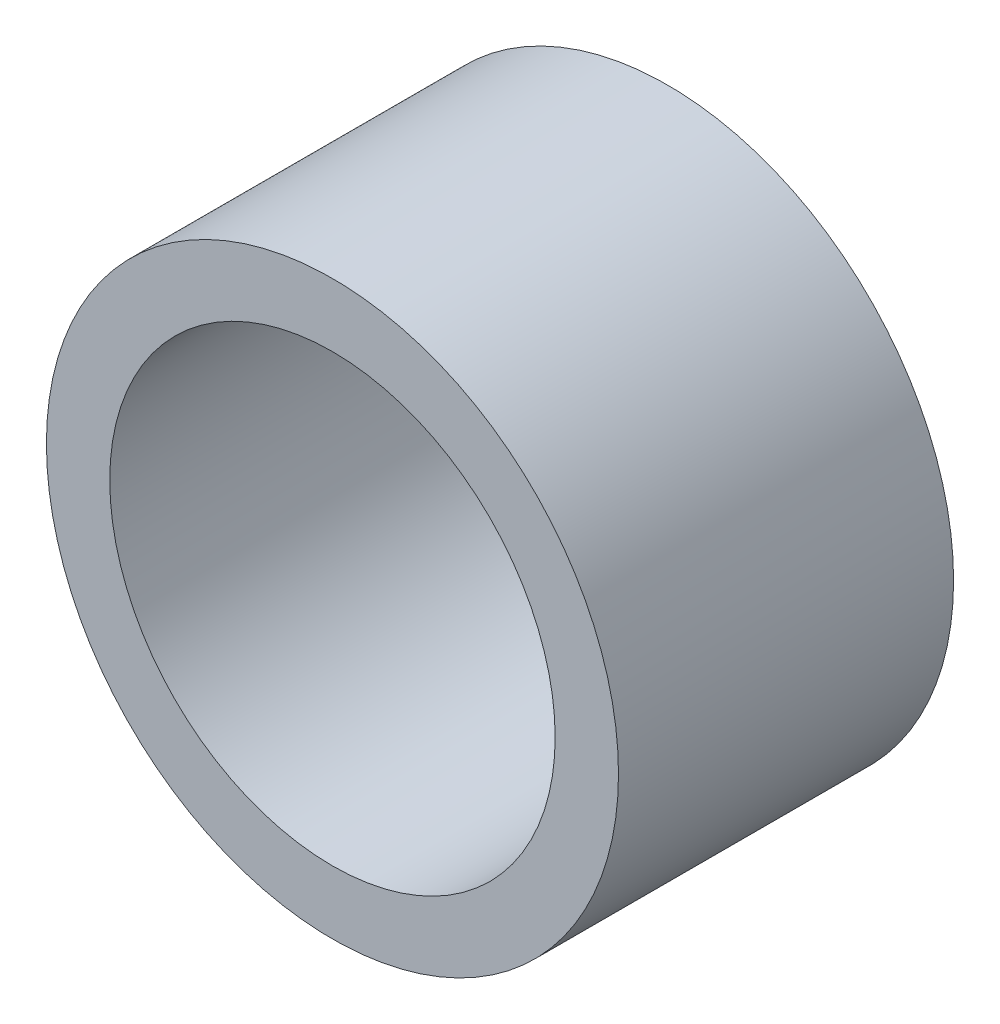
SolidWorks part; units mm, degrees
material "ABS"
ref_plane "Front Plane" through (0, 0, 0) normal (0, 0, 1) x (1, 0, 0)
ref_plane "Top Plane" through (0, 0, 0) normal (0, 1, 0) x (1, 0, 0)
ref_plane "Right Plane" through (0, 0, 0) normal (1, 0, 0) x (0, 0, -1)
sketch "Sketch1" plane through (0, 0, 0) normal (0, 0, 1) x (1, 0, 0)
  circle A0 centre (0, 0) radius 3.5
  circle A1 centre (0, 0) radius 2.725
  dimension "D1" = 7
  dimension "D2" = 5.45
extrude "Boss-Extrude1" add sketch "Sketch1" along normal blind 4.1
equation "\"D2@Sketch1\"=5+\"print_free@Parameters@Parameters.SLDPRT\""
